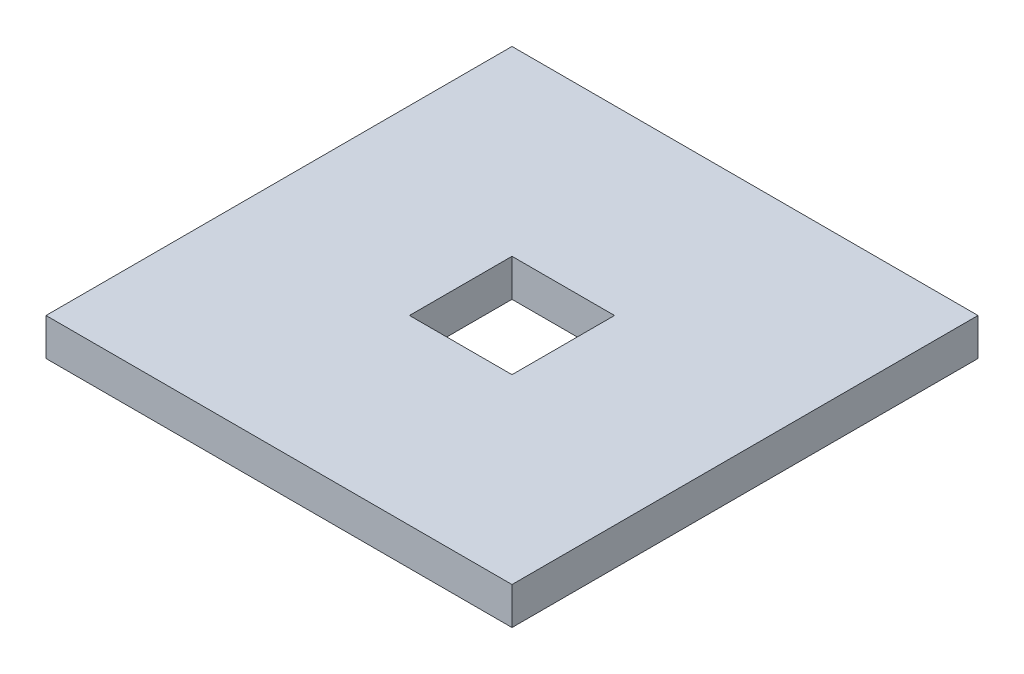
SolidWorks part; units mm, degrees
ref_plane "Front Plane" through (0, 0, 0) normal (0, 0, 1) x (1, 0, 0)
ref_plane "Top Plane" through (0, 0, 0) normal (0, 1, 0) x (1, 0, 0)
ref_plane "Right Plane" through (0, 0, 0) normal (1, 0, 0) x (0, 0, -1)
sketch "Sketch1" plane through (0, 0, 0) normal (0, 1, 0) x (1, 0, 0)
  line L0 (-27.5, 27.5) -> (-125, 125) construction
  line L1 (125, -125) -> (-125, -125)
  line L2 (125, -125) -> (125, 125)
  line L3 (125, 125) -> (-125, 125)
  line L4 (-125, -125) -> (-125, 125)
  line L5 (125, -125) -> (27.5, -27.5) construction
  line L6 (125, 125) -> (27.5, 27.5) construction
  line L7 (27.5, -27.5) -> (-27.5, -27.5)
  line L8 (27.5, -27.5) -> (27.5, 27.5)
  line L9 (27.5, 27.5) -> (-27.5, 27.5)
  line L10 (-27.5, -27.5) -> (-27.5, 27.5)
  line L13 (-27.5, -27.5) -> (-125, -125) construction
  point P0 (0, 0)
  point P5 (0, 0)
  dimension "D1" = 250
  dimension "D2" = 250
  dimension "D3" = 55
extrude "Boss-Extrude1" add sketch "Sketch1" along normal blind 20
